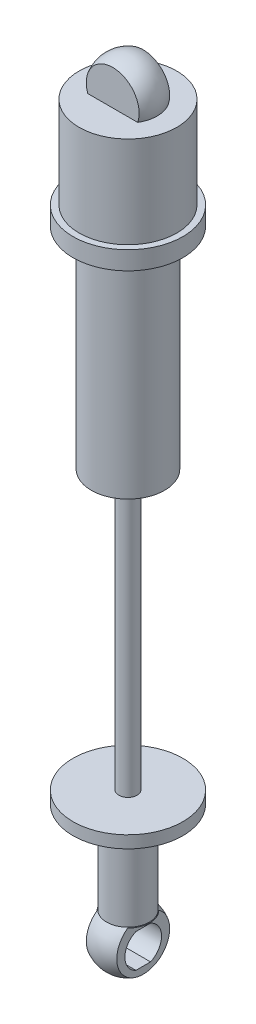
SolidWorks part; units mm, degrees
ref_plane "Спереди" through (0, 0, 0) normal (0, 0, 1) x (1, 0, 0)
ref_plane "Сверху" through (0, 0, 0) normal (0, 1, 0) x (1, 0, 0)
ref_plane "Справа" through (0, 0, 0) normal (1, 0, 0) x (0, 0, -1)
sketch "Эскиз1" plane through (0, 0, 0) normal (0, 0, 1) x (1, 0, 0)
  line L3 (-3.5, 8.5707) -> (-3.5, 23.5707)
  line L4 (-3.5, 23.5707) -> (-9, 23.5707)
  line L5 (-9, 23.5707) -> (-9, 25.5707)
  line L6 (-9, 25.5707) -> (-1.5, 25.5707)
  line L7 (-1.5, 25.5707) -> (-1.5, 71.0707)
  line L8 (-1.5, 71.0707) -> (-6, 71.0707)
  line L9 (-6, 71.0707) -> (-6, 105.5707)
  line L10 (-6, 105.5707) -> (-9, 105.5707)
  line L11 (-9, 105.5707) -> (-9, 108.5707)
  line L12 (-9, 108.5707) -> (-8, 108.5707)
  line L13 (-8, 108.5707) -> (-8, 123.5707)
  line L14 (-8, 123.5707) -> (-4.7914, 123.5707)
  line L15 (0, 125) -> (0, 0)
  line L17 (0, 125) -> (0, 130)
  line L18 (0, 5) -> (-8, 5) construction
  arc A0 (-3.5, 8.5707) -> (0, 0) centre (0, 5) ccw
  arc A1 (0, 130) -> (-4.7914, 123.5707) centre (0, 125) ccw
  dimension "D8" = 5
  dimension "D9" = 5
  dimension "D1" = 120
  dimension "D2" = 8
  dimension "D3" = 9
  dimension "D4" = 6
  dimension "D5" = 1.5
  dimension "D6" = 9
  dimension "D7" = 3.5
  dimension "D10" = 80
  dimension "D11" = 15
  dimension "D12" = 3
  dimension "D13" = 15
  dimension "D14" = 2
  dimension "D15" = 45.5
  dimension "D16" = 5
revolve "Повернуть2" add sketch "Эскиз1" angle 360 about L15
sketch "Эскиз2" plane through (0, 123.5707, 0) normal (0, 1, 0) x (1, 0, 0)
  line L1 (-5, 2.5) -> (5, 2.5)
  line L2 (-5, 2.5) -> (-5, -2.5)
  line L3 (-5, -2.5) -> (5, -2.5)
  line L4 (5, 2.5) -> (5, -2.5)
  line L5 (-5, 2.5) -> (5, -2.5) construction
  line L6 (-5, -2.5) -> (5, 2.5) construction
  circle A0 centre (0, 0) radius 5 construction
  point P0 (0, 0)
  dimension "D1" = 5
extrude "Вырез-Вытянуть1" cut sketch "Эскиз2" along normal blind 10 flip side to cut
sketch "Эскиз3" plane through (0, 0, 0) normal (0, 1, 0) x (1, 0, 0)
  line L1 (2.5, 10) -> (-2.5, 10)
  line L2 (2.5, 10) -> (2.5, -10)
  line L3 (2.5, -10) -> (-2.5, -10)
  line L4 (-2.5, 10) -> (-2.5, -10)
  line L5 (2.5, 10) -> (-2.5, -10) construction
  line L6 (2.5, -10) -> (-2.5, 10) construction
  point P0 (0, 0)
  dimension "D1" = 5
  dimension "D2" = 20
extrude "Вырез-Вытянуть2" cut sketch "Эскиз3" along normal blind 8.5 flip side to cut
sketch "Эскиз4" plane through (2.5, 0, 0) normal (1, 0, 0) x (0, 0, -1)
  line L0 (-1.199, 7.3349) -> (1.199, 7.3349)
  line L1 (-1.199, 1.8349) -> (1.199, 1.8349)
  line L2 (0, 0.6699) -> (0, 1.8349) construction
  line L3 (0, 8.5) -> (0, 7.3349) construction
  line L4 (-2.5495, 8.5) -> (2.5495, 8.5) construction
  line L5 (-2.5495, 8.5) -> (2.5495, 8.5) construction
  arc A1 (-1.199, 7.3349) -> (-1.199, 1.8349) centre (0, 4.5849) ccw
  arc A2 (1.199, 1.8349) -> (1.199, 7.3349) centre (0, 4.5849) ccw
  arc A3 (-2.5495, 8.5) -> (2.5495, 8.5) centre (0, 5) ccw construction
  point P14 (0, 0)
  point P15 (0, 0)
  point P16 (0, 0)
  point P19 (0, 0)
  point P20 (0, 0)
  dimension "D2" = 6
  dimension "D3" = 2.3979
  dimension "D4" = 2.3979
extrude "Вырез-Вытянуть3" cut sketch "Эскиз4" against normal through all
